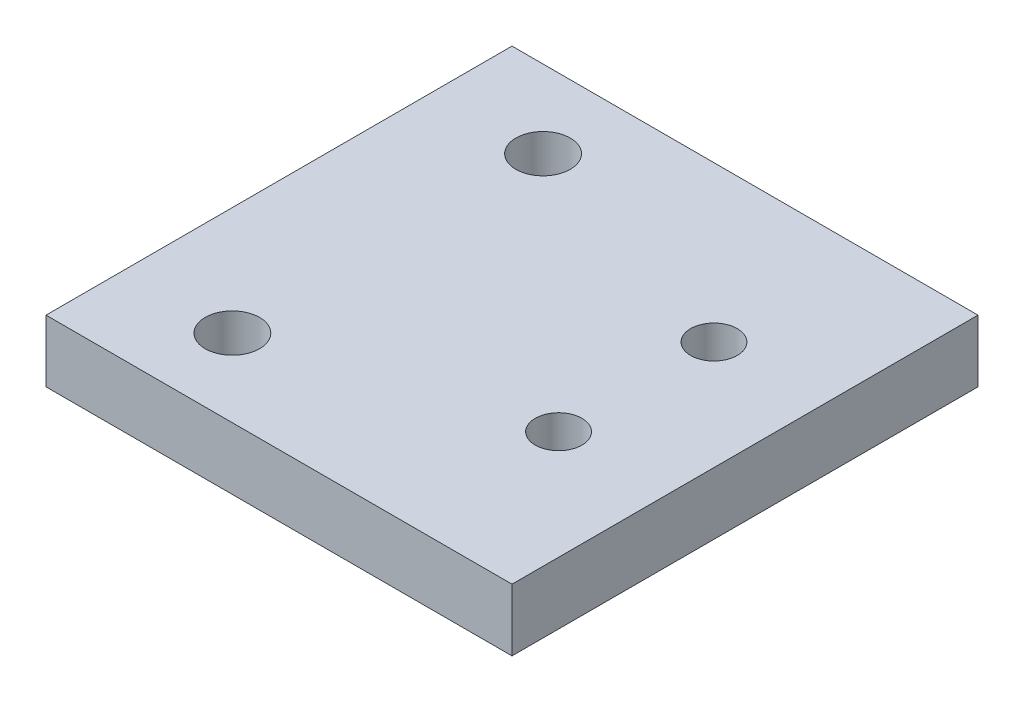
SolidWorks part; units mm, degrees
ref_plane "前视基准面" through (0, 0, 0) normal (0, 0, 1) x (1, 0, 0)
ref_plane "上视基准面" through (0, 0, 0) normal (0, 1, 0) x (1, 0, 0)
ref_plane "右视基准面" through (0, 0, 0) normal (1, 0, 0) x (0, 0, -1)
sketch "草图1" plane through (0, 0, 0) normal (0, 1, 0) x (1, 0, 0)
  line L0 (0, 0) -> (0, 30)
  line L1 (0, 30) -> (30, 30)
  line L2 (30, 30) -> (30, 0)
  line L3 (30, 0) -> (0, 0)
  circle A0 centre (7, 25) radius 1.75
  circle A1 centre (7, 5) radius 1.75
  circle A2 centre (23, 20) radius 1.5
  circle A3 centre (23, 10) radius 1.5
  dimension "D6" = 3.5
  dimension "D7" = 3
  dimension "D1" = 30
  dimension "D2" = 30
  dimension "D3" = 5
  dimension "D4" = 20
  dimension "D5" = 7
  dimension "D8" = 10
  dimension "D9" = 10
  dimension "D10" = 7
extrude "凸台-拉伸1" add sketch "草图1" along normal blind 4
